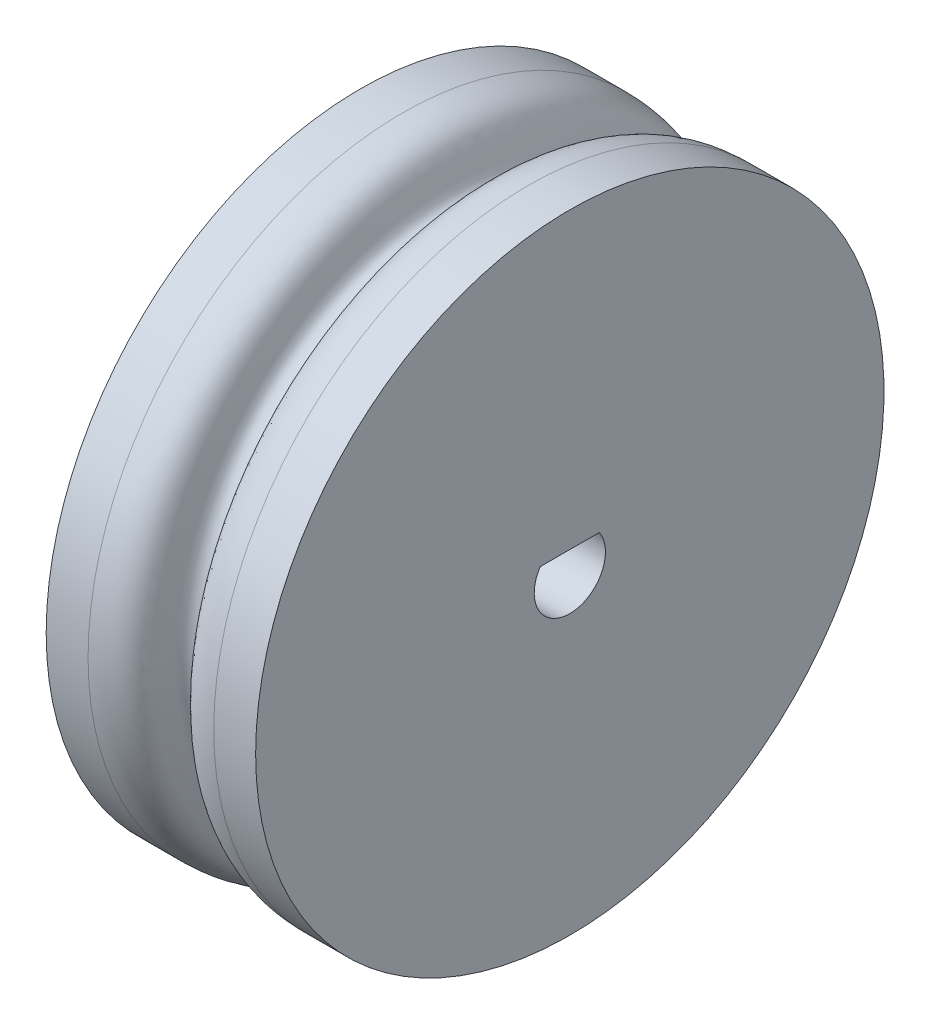
SolidWorks part; units mm, degrees
ref_plane "Front Plane" through (0, 0, 0) normal (0, 0, 1) x (1, 0, 0)
ref_plane "Top Plane" through (0, 0, 0) normal (0, 1, 0) x (1, 0, 0)
ref_plane "Right Plane" through (0, 0, 0) normal (1, 0, 0) x (0, 0, -1)
sketch "Sketch1" plane through (0, 0, 0) normal (0, 0, 1) x (1, 0, 0)
  line L0 (0, 25) -> (0, 0)
  line L1 (0, 0) -> (10, 0)
  line L2 (10, 0) -> (10, 30)
  line L3 (10, 30) -> (6, 30)
  line L4 (0, 25) -> (-37.8825, 25) construction
  circle A0 centre (0, 26.5) radius 1.5 construction
  spline S0 degree 3 poles (0, 25) (2.9351, 25) (0.1918, 30) (6, 30) knots 0 0 0 0 1 1 1 1
  dimension "D4" = 3
  dimension "D1" = 25
  dimension "D2" = 30
  dimension "D3" = 4
  dimension "D5" = 10
revolve "Revolve1" add sketch "Sketch1" angle 360 about L1
mirror "Mirror1" about plane through (0, 25, 0) normal (1, 0, 0) of "Revolve1"
sketch "Sketch2" plane through (10, 0, 0) normal (1, 0, 0) x (0, 0, -1)
  line L0 (-2.8196, 1.9) -> (2.8196, 1.9)
  arc A0 (-2.8196, 1.9) -> (2.8196, 1.9) centre (0, 0) ccw
  point P5 (0, -3.4)
  dimension "D1" = 6.8
  dimension "D2" = 5.3
extrude "Cut-Extrude1" cut sketch "Sketch2" against normal through all
